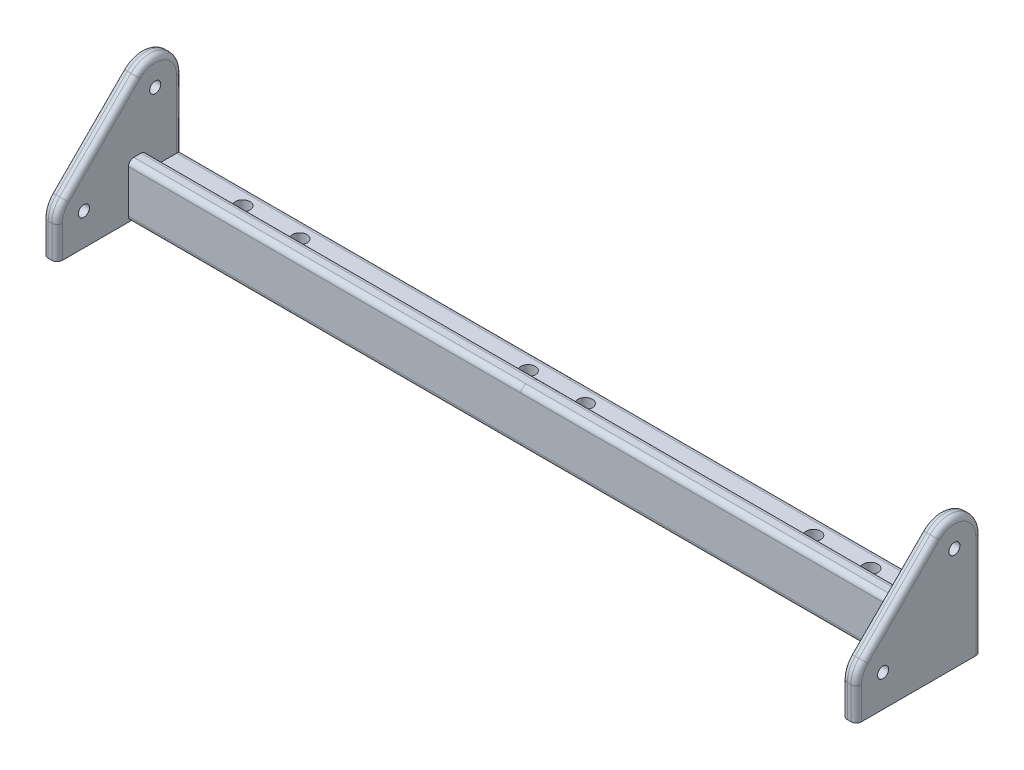
SolidWorks part; units mm, degrees
ref_plane "Plan de face" through (0, 0, 0) normal (0, 0, 1) x (1, 0, 0)
ref_plane "Plan de dessus" through (0, 0, 0) normal (0, 1, 0) x (1, 0, 0)
ref_plane "Plan de droite" through (0, 0, 0) normal (1, 0, 0) x (0, 0, -1)
sketch "Esquisse1" plane through (0, 0, 0) normal (0, 0, 1) x (1, 0, 0)
  line L0 (0, 0) -> (0, 44.2701) construction
  line L1 (0, 0) -> (122.3999, 0) construction
  line L2 (0, 5) -> (122.3999, 5) construction
  line L3 (0, 10) -> (122.3999, 10) construction
  line L4 (0, 0) -> (0, 5) construction
  line L5 (0, 5) -> (15, 5) construction
  line L6 (15, 5) -> (15, 10) construction
  line L7 (15, 10) -> (65, 10) construction
  line L8 (65, 10) -> (65, 5) construction
  line L9 (65, 5) -> (95, 5) construction
  line L10 (95, 5) -> (95, 10) construction
  line L11 (95, 10) -> (110, 10) construction
  line L12 (110, 10) -> (110, 0) construction
  line L13 (110, 0) -> (0, 0) construction
  line L14 (80, 5) -> (80, 10) construction
  line L15 (0, 10) -> (0, 5)
  line L16 (0, 5) -> (15, 5) construction
  line L17 (15, 5) -> (15, 0) construction
  line L18 (15, 0) -> (65, 0) construction
  line L19 (65, 0) -> (65, 5) construction
  line L20 (65, 5) -> (95, 5) construction
  line L21 (95, 5) -> (95, 0) construction
  line L22 (95, 0) -> (110, 0) construction
  line L23 (110, 0) -> (110, 10)
  line L24 (110, 10) -> (0, 10)
  line L25 (0, 5) -> (0, 0)
  line L26 (0, 0) -> (110, 0)
  dimension "D1" = 30
  dimension "D2" = 5
  dimension "D3" = 5
  dimension "D4" = 15
  dimension "D5" = 80
  dimension "D6" = 110
extrude "Boss.-Extru.1" add sketch "Esquisse1" along normal blind 15
sketch "Esquisse2" plane through (110, 0, 0) normal (1, 0, 0) x (0, 0, -1)
  line L0 (0, 0) -> (0, 35.377) construction
  line L1 (0, 0) -> (-43.9624, 0) construction
  line L2 (-36.5, 0) -> (6.4379, 42.9379) construction
  line L3 (1.5, 0) -> (-32.0262, 33.5262) construction
  line L4 (-17.5, 19) -> (20.3247, 19) construction
  line L5 (-17.5, 9) -> (-17.5, 54.8988) construction
  line L8 (-12.8033, 34.3033) -> (-32.8033, 14.3033)
  line L9 (-35, 9) -> (-35, 0)
  line L12 (-35, 0) -> (-15, 0)
  line L13 (0, 29) -> (0, 10)
  line L14 (0, 29) -> (0, 10)
  line L24 (0, 0) -> (0, 10)
  line L25 (0, 10) -> (-15, 10)
  line L26 (-15, 10) -> (-15, 0)
  line L27 (-15, 0) -> (0, 0)
  line L28 (0, 0) -> (0, 10)
  line L29 (0, 10) -> (-15, 10)
  line L30 (-15, 10) -> (-15, 0)
  line L35 (-15, 0) -> (0, 0)
  circle A0 centre (-27.5, 9) radius 1.55
  circle A1 centre (-27.5, 9) radius 10 construction
  circle A2 centre (-7.5, 29) radius 10 construction
  circle A3 centre (-7.5, 29) radius 1.55
  circle A4 centre (-27.5, 9) radius 7.5 construction
  circle A5 centre (-7.5, 29) radius 7.5 construction
  arc A6 (-32.8033, 14.3033) -> (-35, 9) centre (-27.5, 9) ccw
  arc A7 (0, 29) -> (-12.8033, 34.3033) centre (-7.5, 29) ccw
  dimension "D1" = 45
  dimension "D3" = 3.1
  dimension "D4" = 20
  dimension "D5" = 15
  dimension "D7" = 9
  dimension "D2" = 45
  dimension "D6" = 0
extrude "Boss.-Extru.2" add sketch "Esquisse2" along normal blind 4
sketch "Esquisse5" plane through (0, 0, 0) normal (0, -1, 0) x (1, 0, 0)
  line L0 (0, 48.5635) -> (0, -28.5102) construction
  line L1 (-30.4412, 0) -> (140.7754, 0) construction
  line L2 (-6.1805, 5) -> (139.8263, 5) construction
  line L3 (80, 19.9399) -> (80, -9.3402) construction
  line L6 (0, 0) -> (114, 0)
  line L7 (114, 0) -> (114, 35)
  line L8 (114, 35) -> (110, 35)
  line L9 (110, 35) -> (110, 15)
  line L10 (110, 15) -> (0, 15)
  line L11 (0, 15) -> (0, 0)
  line L12 (0, 0) -> (114, 0)
  line L13 (114, 0) -> (114, 35)
  line L14 (114, 35) -> (110, 35)
  line L15 (110, 35) -> (110, 15)
  line L16 (110, 15) -> (0, 15)
  line L17 (0, 15) -> (0, 0)
  circle A0 centre (8, 5) radius 2.05
  circle A1 centre (72, 5) radius 2.05
  circle A2 centre (88, 5) radius 2.05
  dimension "D2" = 8
  dimension "D5" = 4.1
  dimension "D3" = 8
  dimension "D4" = 80
  dimension "D6" = 5
  dimension "D1" = 0
extrude "Enlèv. mat.-Extru.3" cut sketch "Esquisse5" against normal through all contours A0 | A1 | A2
sketch "Esquisse7" plane through (0, 10, 0) normal (0, 1, 0) x (1, 0, 0)
  line L0 (0, -10) -> (110, -10)
  line L4 (110, 0) -> (0, 0)
  line L5 (0, 0) -> (0, -15)
  line L6 (0, -15) -> (110, -15)
  line L7 (110, -15) -> (110, 0)
  line L8 (110, 0) -> (0, 0)
  line L9 (0, 0) -> (0, -15)
  line L10 (0, -15) -> (110, -15)
  line L11 (110, -15) -> (110, 0)
  line M8 (0, 0) -> (0, -15)
  line M9 (0, -15) -> (110, -15)
  line M10 (110, -15) -> (110, 0)
  dimension "D2" = 5
  dimension "D1" = 0
extrude "Boss.-Extru.3" add sketch "Esquisse7" along normal blind 5 contours L0 M8 M9 M10
fillet "Congé1" radius 1.5 15 edges at (55, 10, 10) (55, 10, 0) (55, 15, 10) (55, 15, 15) (55, 0, 15) (114, 14.5, 0) (110, 35.9291, 4.6299) (114, 35.9291, 4.6299) (110, 4.5, 35) (114, 4.5, 35) (110, 11.8701, 34.4291) (114, 11.8701, 34.4291) (110, 19.5, 0) (110, 24.3033, 22.8033) (114, 24.3033, 22.8033)
mirror "Symétrie5" about plane through (0, 5, 15) normal (1, 0, 0) of "Boss.-Extru.1", "Boss.-Extru.2", "Enlèv. mat.-Extru.3", "Boss.-Extru.3", "Congé1"
